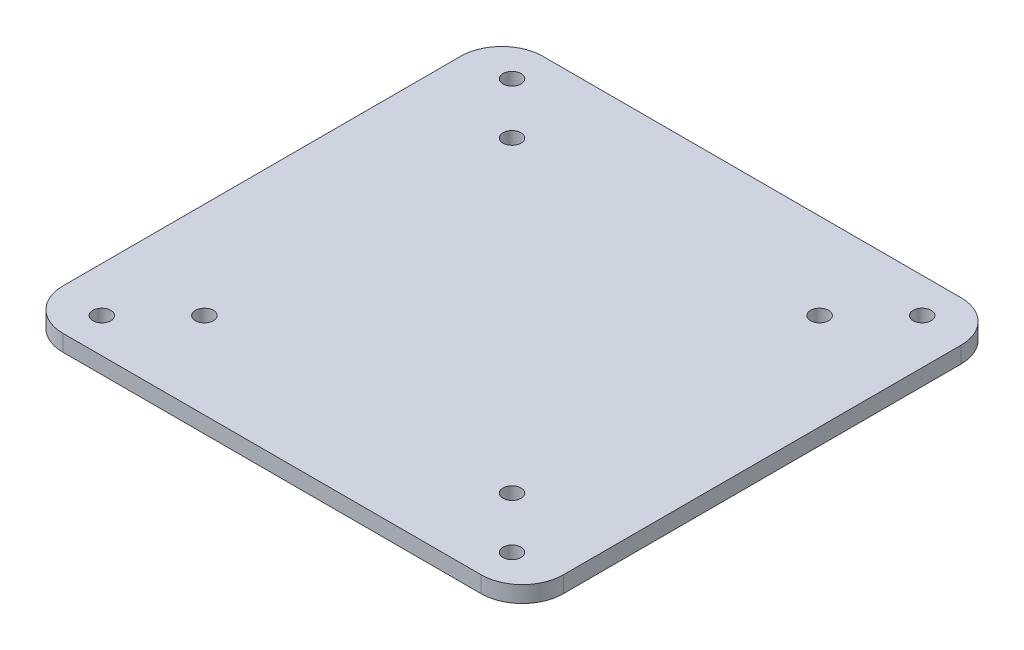
SolidWorks part; units mm, degrees
ref_plane "Front Plane" through (0, 0, 0) normal (0, 0, 1) x (1, 0, 0)
ref_plane "Top Plane" through (0, 0, 0) normal (0, 1, 0) x (1, 0, 0)
ref_plane "Right Plane" through (0, 0, 0) normal (1, 0, 0) x (0, 0, -1)
sketch "Sketch1" plane through (0, 0, 0) normal (0, 1, 0) x (1, 0, 0)
  line L1 (0, 117) -> (122, 117)
  line L2 (0, 117) -> (0, 0)
  line L3 (0, 0) -> (122, 0)
  line L4 (122, 117) -> (122, 0)
  circle A0 centre (111, 108.5) radius 2.2
  circle A1 centre (11, 108.5) radius 2.2
  circle A2 centre (11, 8.5) radius 2.2
  circle A3 centre (111, 8.5) radius 2.2
  circle A4 centre (98.5, 96) radius 2.2
  circle A5 centre (23.5, 96) radius 2.2
  circle A6 centre (23.5, 21) radius 2.2
  circle A7 centre (98.5, 21) radius 2.2
  point P20 (0, 0)
  point P21 (0, 0)
  point P22 (0, 0)
  point P23 (0, 0)
  dimension "D3" = 4.4
  dimension "D4" = 4.4
  dimension "D5" = 4.4
  dimension "D6" = 4.4
  dimension "D9" = 4.4
  dimension "D10" = 4.4
  dimension "D11" = 4.4
  dimension "D12" = 4.4
  dimension "D1" = 122
  dimension "D2" = 117
  dimension "D7" = 21
  dimension "D8" = 8.5
  dimension "D13" = 23.5
  dimension "D14" = 11
  dimension "D15" = 8.5
  dimension "D16" = 21
  dimension "D17" = 11
  dimension "D18" = 23.5
  dimension "D19" = 11
  dimension "D20" = 23.5
  dimension "D21" = 21
  dimension "D22" = 8.5
  dimension "D23" = 21
  dimension "D24" = 23.5
  dimension "D25" = 11
  dimension "D26" = 8.5
extrude "Boss-Extrude1" add sketch "Sketch1" along normal blind 4
fillet "Fillet1" radius 10 4 edges at (0, 2, -117) (122, 2, -117) (122, 2, 0) (0, 2, 0)
